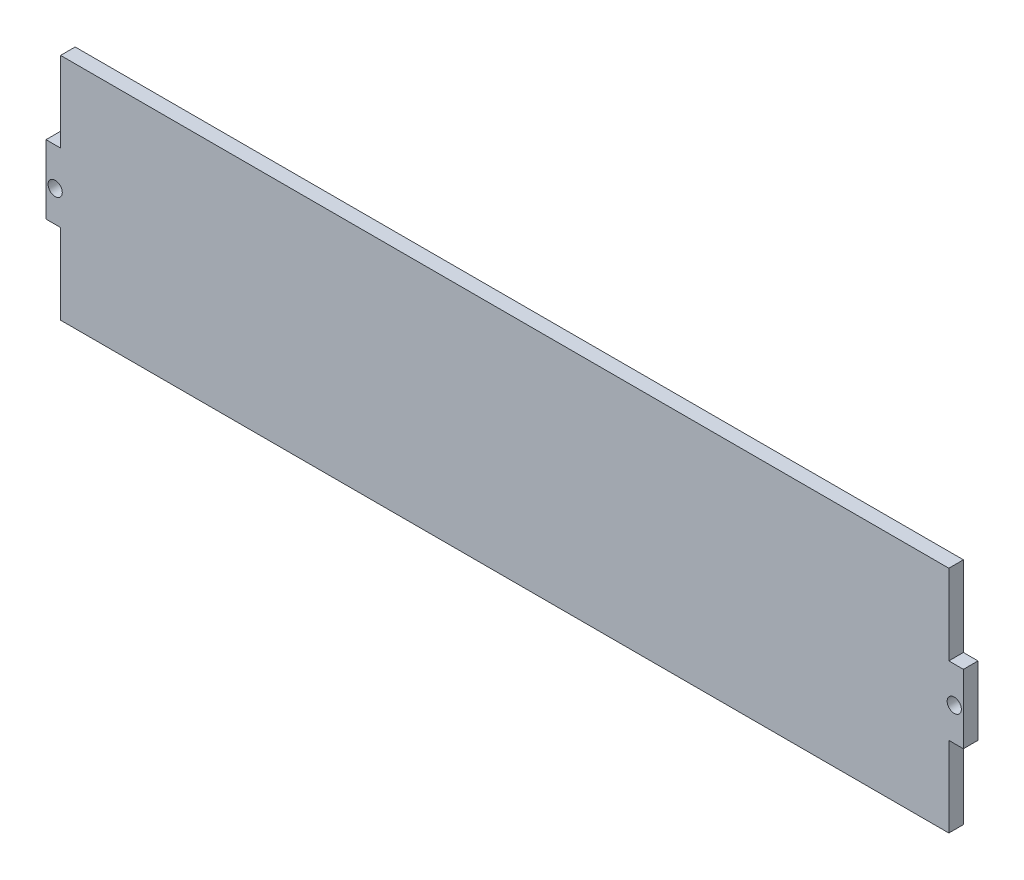
SolidWorks part; units mm, degrees
ref_plane "Front Plane" through (0, 0, 0) normal (0, 0, 1) x (1, 0, 0)
ref_plane "Top Plane" through (0, 0, 0) normal (0, 1, 0) x (1, 0, 0)
ref_plane "Right Plane" through (0, 0, 0) normal (1, 0, 0) x (0, 0, -1)
sketch "Sketch1" plane through (0, 0, 0) normal (0, 0, 1) x (1, 0, 0)
  line L1 (-100, -25) -> (100, -25)
  line L2 (-100, -25) -> (-100, 25)
  line L3 (-100, 25) -> (100, 25)
  line L4 (100, -25) -> (100, 25)
  line L5 (-100, -25) -> (100, 25) construction
  line L6 (-100, 25) -> (100, -25) construction
  point P0 (0, 0)
  point P5 (0, 0)
  point P6 (0, 0)
  dimension "D1" = 200
  dimension "D2" = 50
extrude "Boss-Extrude2" add sketch "Sketch1" along normal blind 3.18 contours L3 L4 L1 L2
sketch "Sketch3" plane through (0, 0, 3.18) normal (0, 0, 1) x (1, 0, 0)
  line L0 (-129.0081, 0) -> (122.1692, 0) construction
  line L1 (-0.8959, 44.6673) -> (1.2774, -63.6895) construction
  line L2 (-100, -25) -> (100, -25) construction
  line L3 (-100, 25) -> (-96.82, 25)
  line L4 (-100, 25) -> (-100, 7.5)
  line L5 (-100, 7.5) -> (-96.82, 7.5)
  line L6 (-96.82, 25) -> (-96.82, 7.5)
  line L7 (-100, -7.5) -> (-96.82, -7.5)
  line L8 (-100, -7.5) -> (-100, -25)
  line L9 (-100, -25) -> (-96.82, -25)
  line L10 (-96.82, -7.5) -> (-96.82, -25)
  line L15 (100, 25) -> (96.82, 25)
  line L16 (100, 25) -> (100, 7.5)
  line L17 (100, 7.5) -> (96.82, 7.5)
  line L18 (96.82, 25) -> (96.82, 7.5)
  line L19 (100, -25) -> (96.82, -25)
  line L20 (100, -25) -> (100, -7.5)
  line L21 (100, -7.5) -> (96.82, -7.5)
  line L22 (96.82, -25) -> (96.82, -7.5)
  line L23 (-100, 25) -> (100, 25) construction
  line L24 (100, -25) -> (100, 25) construction
  line L25 (-100, -25) -> (-100, 25) construction
  dimension "D1" = 15
  dimension "D2" = 15
  dimension "D3" = 3.18
  dimension "D4" = 3.18
  dimension "D5" = 3.18
  dimension "D6" = 3.18
extrude "Cut-Extrude1" cut sketch "Sketch3" against normal through all
sketch "Sketch4" plane through (0, 0, 3.18) normal (0, 0, 1) x (1, 0, 0)
  line L0 (-132.4612, -0.9565) -> (122.1308, 0.8819) construction
  line L1 (-0.108, 49.3769) -> (0.2024, -92.5114) construction
  line L2 (-100, -7.5) -> (-100, 7.5) construction
  circle A0 centre (-98, -0.7076) radius 1.55
  circle A1 centre (98.0022, -0.2788) radius 1.55
  dimension "D1" = 3.1
  dimension "D2" = 2
extrude "Cut-Extrude2" cut sketch "Sketch4" against normal through all
